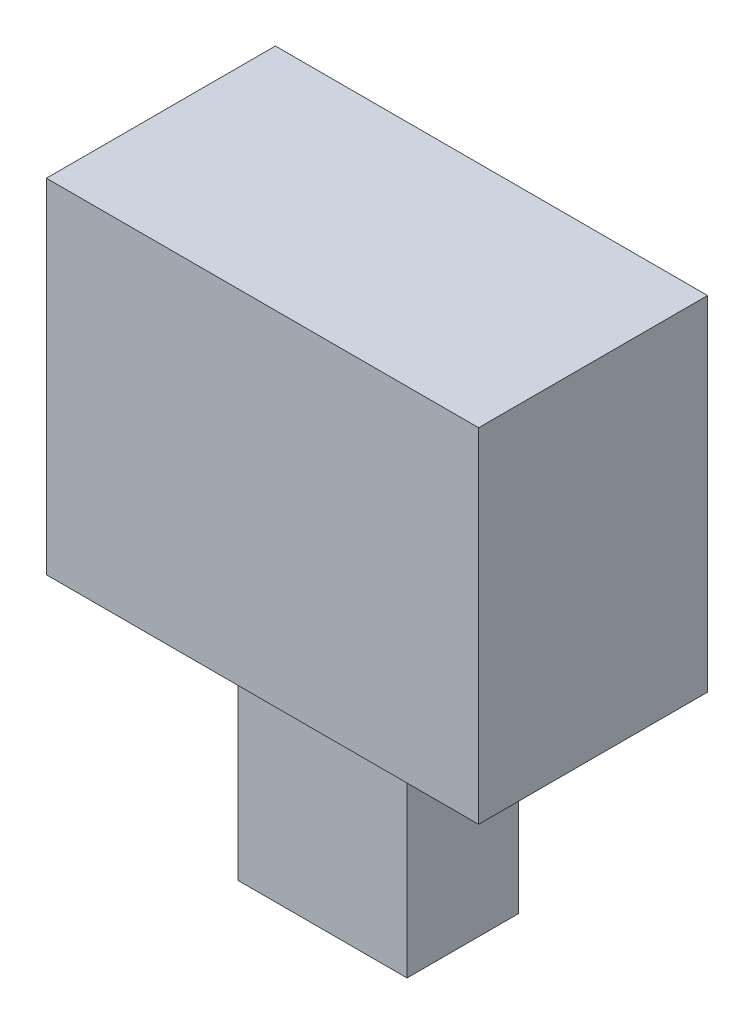
SolidWorks part; units mm, degrees
ref_plane "Front Plane" through (0, 0, 0) normal (0, 0, 1) x (1, 0, 0)
ref_plane "Top Plane" through (0, 0, 0) normal (0, 1, 0) x (1, 0, 0)
ref_plane "Right Plane" through (0, 0, 0) normal (1, 0, 0) x (0, 0, -1)
sketch "Sketch1" plane through (0, 0, 0) normal (0, 1, 0) x (1, 0, 0)
  line L4 (-7.375, 4.75) -> (-7.375, -5)
  line L5 (-7.375, -5) -> (7.375, -5)
  line L6 (7.375, -5) -> (7.375, 4.75)
  line L9 (7.375, 4.75) -> (-7.375, 4.75)
  point P1 (0, 0)
  point P2 (0, 0)
  point P4 (0, 0)
  point P6 (-12.8712, 9.7762)
  point P7 (-9.6256, 3.2851)
  dimension "D1" = 14.75
  dimension "D2" = 7.375
  dimension "D5" = 9.75
  dimension "D6" = 14.75
extrude "Boss-Extrude1" add sketch "Sketch1" along normal blind 50 contours L6 L9 L4 L5
sketch "Sketch3" plane through (0, 0, 0) normal (1, 0, 0) x (0, 0, -1)
  line L0 (-5, 50) -> (-5, 0) construction
  line L2 (-5.25, 20) -> (-10.25, 20)
  line L3 (-10.25, 20) -> (9.75, 20)
  line L4 (9.75, 20) -> (9.75, 50)
  line L7 (-10.25, 50) -> (-10.25, 20)
  line L8 (-10.25, 50) -> (9.75, 50)
  line L9 (4.75, 50) -> (4.75, 0) construction
  point P0 (0, 0)
  dimension "D1" = 5.25
  dimension "D2" = 5
  dimension "D3" = 20
extrude "Boss-Extrude2" add sketch "Sketch3" along normal blind 18.875 and the other way blind 18.875 contours L8 L7 L2 L3 L4
